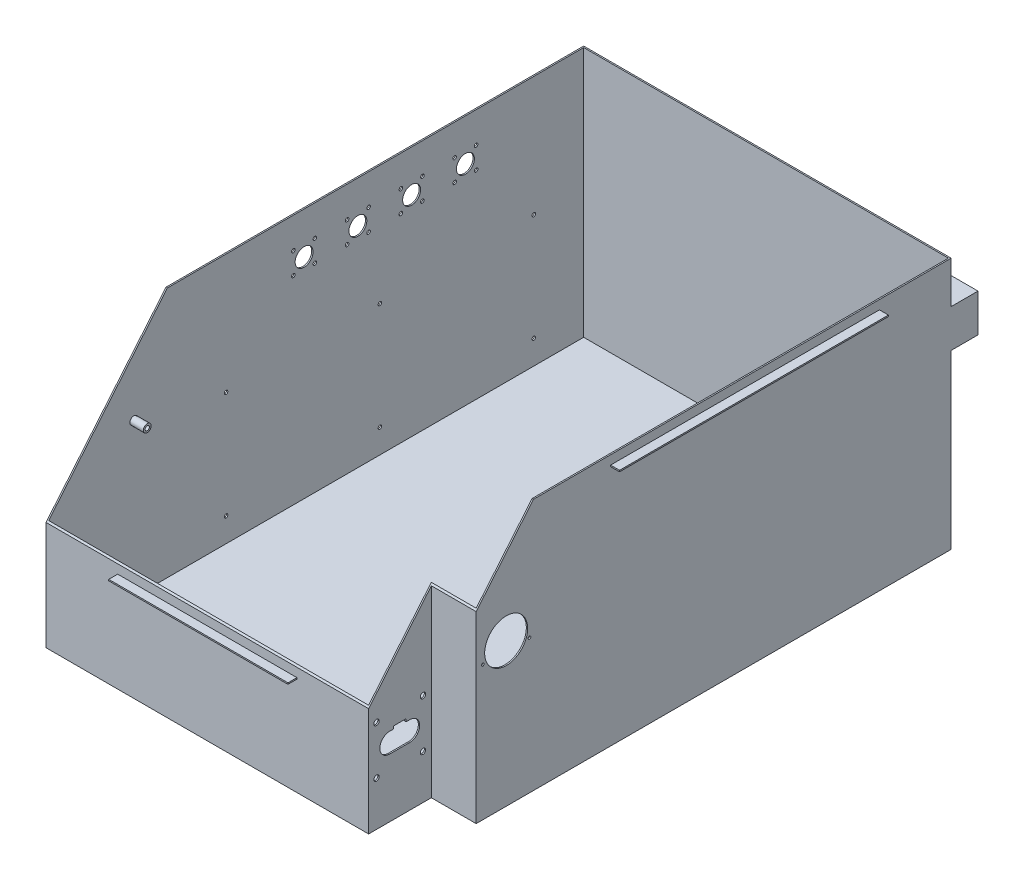
SolidWorks part; units mm, degrees
ref_plane "Front Plane" through (0, 0, 0) normal (0, 0, 1) x (1, 0, 0)
ref_plane "Top Plane" through (0, 0, 0) normal (0, 1, 0) x (1, 0, 0)
ref_plane "Right Plane" through (0, 0, 0) normal (1, 0, 0) x (0, 0, -1)
sketch "Sketch1" plane through (0, 0, 0) normal (0, 1, 0) x (1, 0, 0)
  line L1 (-205, 237.8263) -> (205, 237.8263)
  line L2 (-205, 237.8263) -> (-205, -362.1737)
  line L3 (-205, -362.1737) -> (155, -362.1737)
  line L4 (205, 237.8263) -> (205, -292.1737)
  line L6 (205, -292.1737) -> (155, -292.1737)
  line L7 (155, -292.1737) -> (155, -362.1737)
  line L8 (0, -55) -> (0, 55) construction
  point P1 (0, 237.8263)
  dimension "D1" = 600
  dimension "D2" = 410
  dimension "D5" = 70
  dimension "D6" = 50
extrude "Boss-Extrude1" add sketch "Sketch1" along normal blind 1.5
sketch "Sketch2" plane through (0, 1.5, 0) normal (0, 1, 0) x (1, 0, 0)
  line L60 (-203.5, 236.3263) -> (-203.5, -360.6737)
  line L61 (-203.5, -360.6737) -> (153.5, -360.6737)
  line L62 (153.5, -360.6737) -> (153.5, -290.6737)
  line L63 (153.5, -290.6737) -> (203.5, -290.6737)
  line L64 (203.5, -290.6737) -> (203.5, 236.3263)
  line L65 (203.5, 236.3263) -> (-203.5, 236.3263)
  line L66 (-205, 237.8263) -> (-205, -362.1737)
  line L67 (-205, -362.1737) -> (155, -362.1737)
  line L68 (155, -362.1737) -> (155, -292.1737)
  line L69 (155, -292.1737) -> (205, -292.1737)
  line L70 (205, -292.1737) -> (205, 237.8263)
  line L71 (205, 237.8263) -> (-205, 237.8263)
  line L72 (-205, 237.8263) -> (-205, -362.1737)
  line L73 (-205, -362.1737) -> (155, -362.1737)
  line L74 (155, -362.1737) -> (155, -292.1737)
  line L75 (155, -292.1737) -> (205, -292.1737)
  line L76 (205, -292.1737) -> (205, 237.8263)
  line L77 (205, 237.8263) -> (-205, 237.8263)
  dimension "D1" = 0
  dimension "D2" = 1.5
extrude "Boss-Extrude2" add sketch "Sketch2" along normal blind 280
sketch "Sketch3" plane through (-205, 0, 0) normal (-1, 0, 0) x (0, 0, 1)
  line L3 (362.1737, 281.5) -> (362.1737, 0) construction
  line L4 (362.1737, 121.1176) -> (228.1952, 281.5)
  line L6 (-237.8263, 281.5) -> (362.1737, 281.5) construction
  line L9 (362.1737, 281.5) -> (362.1737, 121.1176)
  line L10 (228.1952, 281.5) -> (362.1737, 281.5)
sketch "Sketch4" plane through (0, 0, -237.8263) normal (0, 0, -1) x (-1, 0, 0)
  line L0 (-205, 281.5) -> (-205, 0) construction
  line L1 (-205, 234.6761) -> (205, 234.6761)
  line L2 (-205, 234.6761) -> (-205, 192.2905)
  line L3 (-205, 192.2905) -> (205, 192.2905)
  line L4 (205, 234.6761) -> (205, 192.2905)
  line L5 (205, 281.5) -> (205, 0) construction
extrude "Boss-Extrude3" add sketch "Sketch4" along normal blind 30
extrude "Cut-Extrude1" cut sketch "Sketch3" against normal through all both and the other way through all
sketch "Sketch5" plane through (-205, 0, 0) normal (-1, 0, 0) x (0, 0, 1)
  line L0 (-116.3263, 223.1259) -> (-116.3263, 247.1259) construction
  line L5 (-116.3263, 223.1259) -> (-92.3263, 223.1259) construction
  line L6 (-116.3263, 247.1259) -> (-92.3263, 247.1259) construction
  line L7 (-92.3263, 223.1259) -> (-92.3263, 247.1259) construction
  line L8 (-116.3263, 223.1259) -> (-92.3263, 247.1259) construction
  line L9 (-116.3263, 247.1259) -> (-92.3263, 223.1259) construction
  line L10 (-56.3263, 223.1259) -> (-56.3263, 247.1259) construction
  line L11 (-56.3263, 223.1259) -> (-32.3263, 223.1259) construction
  line L12 (-56.3263, 247.1259) -> (-32.3263, 247.1259) construction
  line L13 (-32.3263, 223.1259) -> (-32.3263, 247.1259) construction
  line L14 (-56.3263, 223.1259) -> (-32.3263, 247.1259) construction
  line L15 (-56.3263, 247.1259) -> (-32.3263, 223.1259) construction
  line L16 (3.6737, 223.1259) -> (3.6737, 247.1259) construction
  line L17 (3.6737, 223.1259) -> (27.6737, 223.1259) construction
  line L18 (3.6737, 247.1259) -> (27.6737, 247.1259) construction
  line L19 (27.6737, 223.1259) -> (27.6737, 247.1259) construction
  line L20 (3.6737, 223.1259) -> (27.6737, 247.1259) construction
  line L21 (3.6737, 247.1259) -> (27.6737, 223.1259) construction
  line L22 (63.6737, 223.1259) -> (63.6737, 247.1259) construction
  line L23 (63.6737, 223.1259) -> (87.6737, 223.1259) construction
  line L24 (63.6737, 247.1259) -> (87.6737, 247.1259) construction
  line L25 (87.6737, 223.1259) -> (87.6737, 247.1259) construction
  line L26 (63.6737, 223.1259) -> (87.6737, 247.1259) construction
  line L27 (63.6737, 247.1259) -> (87.6737, 223.1259) construction
  line L28 (-236.3263, 281.5) -> (-236.3263, 1.5) construction
  circle A0 centre (-116.3263, 247.1259) radius 2
  circle A1 centre (-116.3263, 223.1259) radius 2
  circle A2 centre (-92.3263, 223.1259) radius 2
  circle A3 centre (-92.3263, 247.1259) radius 2
  circle A4 centre (-104.3263, 235.1259) radius 10
  circle A5 centre (-56.3263, 247.1259) radius 2
  circle A6 centre (-56.3263, 223.1259) radius 2
  circle A7 centre (-32.3263, 223.1259) radius 2
  circle A8 centre (-32.3263, 247.1259) radius 2
  circle A9 centre (-44.3263, 235.1259) radius 10
  circle A10 centre (3.6737, 247.1259) radius 2
  circle A11 centre (3.6737, 223.1259) radius 2
  circle A12 centre (27.6737, 223.1259) radius 2
  circle A13 centre (27.6737, 247.1259) radius 2
  circle A14 centre (15.6737, 235.1259) radius 10
  circle A15 centre (63.6737, 247.1259) radius 2
  circle A16 centre (63.6737, 223.1259) radius 2
  circle A17 centre (87.6737, 223.1259) radius 2
  circle A18 centre (87.6737, 247.1259) radius 2
  circle A19 centre (75.6737, 235.1259) radius 10
  point P9 (-104.3263, 235.1259)
  point P24 (-44.3263, 235.1259)
  point P38 (15.6737, 235.1259)
  point P52 (75.6737, 235.1259)
  dimension "D2" = 20
  dimension "D5" = 4
  dimension "D1" = 24
  dimension "D3" = 24
  dimension "D4" = 24
  dimension "D7" = 120
  dimension "D6" = 4
sketch "Sketch6" plane through (-203.5, 0, 0) normal (1, 0, 0) x (0, 0, -1)
  arc A0 (151.1392, 167.4539) -> (156.7272, 167.4539) centre (153.9332, 167.4539) ccw construction
  arc A1 (-68.8756, 167.4539) -> (-63.2876, 167.4539) centre (-66.0816, 167.4539) ccw construction
  arc A2 (-178.883, 167.4539) -> (-173.295, 167.4539) centre (-176.089, 167.4539) ccw construction
  arc A3 (151.1392, 167.4539) -> (156.7272, 167.4539) centre (153.9332, 167.4539) ccw
  arc A4 (-68.8756, 167.4539) -> (-63.2876, 167.4539) centre (-66.0816, 167.4539) ccw
  arc A5 (-178.883, 167.4539) -> (-173.295, 167.4539) centre (-176.089, 167.4539) ccw
  circle A6 centre (-176.089, 167.4539) radius 2.794
  circle A7 centre (-176.089, 167.4539) radius 4.5
  circle A8 centre (-64.4633, 167.4539) radius 4.5
  circle A9 centre (-64.4633, 167.4539) radius 2.794
  circle A10 centre (155.5515, 167.4539) radius 2.794
  circle A11 centre (155.5515, 167.4539) radius 4.5
  dimension "D1" = 9
extrude "Boss-Extrude4" [suppressed] add sketch "Sketch6" along normal blind 50 contours A4 A9 | A8 | A7 | A6 | A11 | A10
sketch "Sketch8" plane through (-203.5, 0, 0) normal (1, 0, 0) x (0, 0, -1)
  line L0 (236.3263, 1.5) -> (-360.6737, 1.5) construction
  line L1 (-360.6737, 122.9132) -> (-360.6737, 1.5) construction
  circle A0 centre (-265.6737, 172.2) radius 2.39
  circle A1 centre (-265.6737, 172.2) radius 4.39
  circle A2 centre (-265.6737, 16.5) radius 2.39
  circle A3 centre (-265.6737, 16.5) radius 4.39
  dimension "D3" = 4.78
  dimension "D4" = 2
  dimension "D1" = 155.7
  dimension "D2" = 15
  dimension "D5" = 95
extrude "Boss-Extrude5" add sketch "Sketch8" along normal blind 15
sketch "Sketch10" plane through (153.5, 0, 0) normal (-1, 0, 0) x (0, 0, 1)
  line L0 (316.1737, 86.5) -> (321.4237, 86.5) construction
  line L1 (316.1737, 66.5) -> (338.6737, 66.5) construction
  line L2 (338.6737, 76.5) -> (316.1737, 76.5) construction
  line L3 (360.6737, 1.5) -> (290.6737, 1.5) construction
  line L5 (321.4237, 86.5) -> (321.4237, 89.5) construction
  line L6 (321.4237, 89.5) -> (333.4237, 89.5) construction
  line L7 (333.4237, 86.5) -> (333.4237, 89.5) construction
  line L8 (360.6737, 122.9132) -> (360.6737, 1.5) construction
  line L9 (333.4237, 86.5) -> (338.6737, 86.5) construction
  line L10 (320.4237, 90.5) -> (334.4237, 90.5)
  line L11 (334.4237, 87.5) -> (334.4237, 90.5)
  line L12 (334.4237, 87.5) -> (338.6737, 87.5)
  line L13 (316.1737, 65.5) -> (338.6737, 65.5)
  line L14 (316.1737, 87.5) -> (320.4237, 87.5)
  line L15 (320.4237, 87.5) -> (320.4237, 90.5)
  line L17 (301.4737, 49.55) -> (353.3737, 49.55) construction
  line L18 (301.4737, 49.55) -> (301.4737, 103.45) construction
  line L19 (301.4737, 103.45) -> (353.3737, 103.45) construction
  line L20 (353.3737, 49.55) -> (353.3737, 103.45) construction
  line L21 (301.4737, 49.55) -> (353.3737, 103.45) construction
  line L22 (301.4737, 103.45) -> (353.3737, 49.55) construction
  arc A0 (316.1737, 86.5) -> (316.1737, 66.5) centre (316.1737, 76.5) ccw construction
  arc A1 (338.6737, 66.5) -> (338.6737, 86.5) centre (338.6737, 76.5) ccw construction
  arc A2 (338.6737, 65.5) -> (338.6737, 87.5) centre (338.6737, 76.5) ccw
  arc A3 (316.1737, 87.5) -> (316.1737, 65.5) centre (316.1737, 76.5) ccw
  circle A4 centre (301.4737, 103.45) radius 3
  circle A5 centre (353.3737, 103.45) radius 3
  circle A6 centre (301.4737, 49.55) radius 3
  circle A7 centre (353.3737, 49.55) radius 3
  point P12 (327.4237, 89.5)
  point P13 (327.4237, 76.5)
  point P26 (327.4237, 76.5)
  dimension "D1" = 65
  dimension "D2" = 22.5
  dimension "D6" = 20
  dimension "D10" = 6
  dimension "D3" = 22
  dimension "D4" = 12
  dimension "D5" = 3
  dimension "D8" = 51.9
  dimension "D9" = 53.9
  dimension "D7" = 1
extrude "Cut-Extrude2" cut sketch "Sketch10" against normal up to surface (1.5 mm away)
sketch "Sketch11" plane through (153.5, 0, 0) normal (-1, 0, 0) x (0, 0, 1)
  line L0 (298.4737, 103.43) -> (298.4737, 49.53) construction
  line L13 (316.1737, 66.5) -> (338.6737, 66.5) construction
  line L14 (316.1737, 86.5) -> (321.4237, 86.5) construction
  line L15 (316.1737, 66.5) -> (338.6737, 66.5)
  line L19 (316.1737, 86.5) -> (318.4237, 86.5)
  line L20 (334.4237, 90.5) -> (320.4237, 90.5)
  line L21 (334.4237, 90.5) -> (320.4237, 90.5)
  line L22 (334.4237, 87.5) -> (334.4237, 90.5)
  line L23 (334.4237, 87.5) -> (334.4237, 90.5)
  line L28 (330.4237, 86.5) -> (321.4237, 86.5)
  line L29 (316.2509, 66) -> (338.7144, 66)
  line L30 (330.9237, 86) -> (320.7529, 86)
  line L31 (330.9237, 86) -> (330.9237, 91)
  line L32 (330.9237, 91) -> (317.9237, 91)
  line L33 (317.9237, 91) -> (317.9237, 87)
  line L34 (316.2509, 87) -> (317.9237, 87)
  line L36 (298.4737, 103.43) -> (350.3737, 103.43) construction
  line L43 (334.4237, 90.5) -> (320.4237, 90.5)
  line L44 (334.4237, 90.5) -> (320.4237, 90.5)
  line L45 (334.4237, 87.5) -> (334.4237, 90.5)
  line L46 (334.4237, 87.5) -> (334.4237, 90.5)
  line L47 (338.6737, 87.5) -> (334.4237, 87.5)
  line L48 (338.6737, 87.5) -> (334.4237, 87.5)
  line L49 (316.1737, 65.5) -> (338.6737, 65.5)
  line L50 (316.1737, 65.5) -> (338.6737, 65.5)
  line L51 (320.4237, 87.5) -> (316.1737, 87.5)
  line L52 (320.4237, 87.5) -> (316.1737, 87.5)
  line L53 (320.4237, 90.5) -> (320.4237, 87.5)
  line L54 (320.4237, 90.5) -> (320.4237, 87.5)
  line L55 (334.4237, 90.5) -> (320.4237, 90.5)
  line L56 (334.4237, 90.5) -> (320.4237, 90.5)
  line L57 (334.4237, 87.5) -> (334.4237, 90.5)
  line L58 (334.4237, 87.5) -> (334.4237, 90.5)
  line L59 (338.6737, 87.5) -> (334.4237, 87.5)
  line L60 (338.6737, 87.5) -> (334.4237, 87.5)
  line L61 (316.1737, 65.5) -> (338.6737, 65.5)
  line L62 (316.1737, 65.5) -> (338.6737, 65.5)
  line L63 (320.4237, 87.5) -> (316.1737, 87.5)
  line L64 (320.4237, 87.5) -> (316.1737, 87.5)
  line L65 (320.4237, 90.5) -> (320.4237, 87.5)
  line L66 (320.4237, 90.5) -> (320.4237, 87.5)
  line L67 (330.4237, 86.5) -> (330.4237, 90.5) construction
  line L68 (330.4237, 90.5) -> (318.4237, 90.5) construction
  line L69 (318.4237, 90.5) -> (318.4237, 86.5) construction
  line L70 (338.6737, 87.5) -> (334.4237, 87.5)
  line L71 (338.6737, 87.5) -> (334.4237, 87.5)
  line L72 (316.1737, 65.5) -> (338.6737, 65.5)
  line L73 (316.1737, 65.5) -> (338.6737, 65.5)
  line L74 (320.4237, 87.5) -> (316.1737, 87.5)
  line L75 (320.4237, 87.5) -> (316.1737, 87.5)
  line L76 (320.4237, 90.5) -> (320.4237, 87.5)
  line L77 (320.4237, 90.5) -> (320.4237, 87.5)
  arc A4 (338.7144, 66) -> (320.7529, 86) centre (336.1498, 81.7622) ccw
  arc A5 (338.6737, 65.5) -> (338.6737, 87.5) centre (338.6737, 76.5) ccw
  arc A7 (338.6737, 65.5) -> (338.6737, 87.5) centre (338.6737, 76.5) ccw
  arc A9 (316.2509, 87) -> (316.2509, 66) centre (312.9721, 76.5) ccw
  circle A10 centre (298.4737, 103.43) radius 3
  circle A11 centre (298.4737, 49.53) radius 3
  circle A12 centre (350.3737, 103.43) radius 3
  circle A13 centre (350.3737, 49.53) radius 3
  arc A16 (338.6737, 66.5) -> (321.4237, 86.5) centre (336.1498, 81.7622) ccw construction
  arc A17 (338.6737, 65.5) -> (338.6737, 87.5) centre (338.6737, 76.5) ccw
  arc A18 (316.1737, 87.5) -> (316.1737, 65.5) centre (316.1737, 76.5) ccw
  arc A19 (316.1737, 87.5) -> (316.1737, 65.5) centre (316.1737, 76.5) ccw
  arc A20 (316.1737, 86.5) -> (316.1737, 66.5) centre (312.9721, 76.5) ccw construction
  arc A21 (338.6737, 65.5) -> (338.6737, 87.5) centre (338.6737, 76.5) ccw
  arc A22 (316.1737, 87.5) -> (316.1737, 65.5) centre (316.1737, 76.5) ccw
  arc A23 (316.1737, 87.5) -> (316.1737, 65.5) centre (316.1737, 76.5) ccw
  arc A24 (338.6737, 65.5) -> (338.6737, 87.5) centre (338.6737, 76.5) ccw
  arc A25 (338.6737, 65.5) -> (338.6737, 87.5) centre (338.6737, 76.5) ccw
  arc A26 (316.1737, 87.5) -> (316.1737, 65.5) centre (316.1737, 76.5) ccw
  arc A27 (316.1737, 87.5) -> (316.1737, 65.5) centre (316.1737, 76.5) ccw
  dimension "D5" = 6
  dimension "D6" = 51.9
  dimension "D7" = 53.9
  dimension "D1" = 0
  dimension "D2" = 0
  dimension "D3" = 0
  dimension "D4" = 0.5
extrude "Cut-Extrude3" [suppressed] cut sketch "Sketch11" against normal through all
sketch "Sketch14" plane through (153.5, 0, 0) normal (-1, 0, 0) x (0, 0, 1)
  line L0 (362.1737, 121.1176) -> (362.1737, 0) construction
  line L1 (362.1737, 0) -> (292.1737, 0) construction
  circle A0 centre (297.2737, 103.43) radius 3
  circle A1 centre (349.1737, 103.43) radius 3
  circle A2 centre (349.1737, 49.53) radius 3
  circle A3 centre (297.2737, 49.53) radius 3
  dimension "D5" = 6
  dimension "D1" = 51.9
  dimension "D2" = 53.9
  dimension "D3" = 13
  dimension "D4" = 103.43
extrude "Cut-Extrude4" [suppressed] cut sketch "Sketch14" against normal up to surface (1.5 mm away)
sketch "Sketch15" plane through (203.5, 0, 0) normal (-1, 0, 0) x (0, 0, 1)
  line L1 (-151.3263, 252.1363) -> (-136.3263, 252.1363)
  line L2 (-151.3263, 252.1363) -> (-151.3263, 250.6363)
  line L3 (-151.3263, 250.6363) -> (-136.3263, 250.6363)
  line L4 (-136.3263, 252.1363) -> (-136.3263, 250.6363)
  line L5 (-236.3263, 281.5) -> (-236.3263, 1.5) construction
  line L6 (126.6737, 252.1363) -> (146.6737, 252.1363)
  line L7 (126.6737, 250.6363) -> (146.6737, 250.6363)
  line L8 (126.6737, 252.1363) -> (126.6737, 250.6363)
  line L9 (146.6737, 252.1363) -> (146.6737, 250.6363)
  dimension "D1" = 1.5
  dimension "D2" = 15
  dimension "D3" = 85
  dimension "D4" = 363
  dimension "D5" = 20
extrude "Boss-Extrude6" add sketch "Sketch15" along normal blind 13
ref_plane "Plane1" through (0, 0, -131.3263) normal (0, 0, -1) x (-1, 0, 0)
sketch "Sketch17" plane through (0, 0, -136.3263) normal (0, 0, 1) x (1, 0, 0)
  line L0 (203.5, 250.6363) -> (203.5, 235.6363)
  line L1 (203.5, 281.5) -> (203.5, 206.7085) construction
  line L2 (203.5, 235.6363) -> (190.5, 250.6363)
  line L3 (190.5, 250.6363) -> (203.5, 250.6363)
  dimension "D1" = 15
extrude "Boss-Extrude7" add sketch "Sketch17" against normal blind 1.5
ref_plane "Plane2" through (0, 0, 126.6737) normal (0, 0, 1) x (1, 0, 0)
sketch "Sketch18" plane through (0, 0, 126.6737) normal (0, 0, 1) x (1, 0, 0)
  line L0 (203.5, 250.6363) -> (203.5, 235.6363)
  line L1 (203.5, 281.5) -> (203.5, 206.7085) construction
  line L2 (203.5, 235.6363) -> (190.5, 250.6363)
  line L3 (190.5, 250.6363) -> (203.5, 250.6363)
  dimension "D1" = 15
extrude "Boss-Extrude8" add sketch "Sketch18" along normal blind 1.5
sketch "Sketch20" plane through (0, 252.1363, 0) normal (0, 1, 0) x (1, 0, 0)
  line L1 (190.5, 151.3263) -> (203.5, 151.3263) construction
  line L2 (190.5, 136.3263) -> (190.5, 151.3263) construction
  line L3 (190.5, -146.6737) -> (203.5, -146.6737) construction
  line L4 (190.5, -146.6737) -> (190.5, -126.6737) construction
  circle A0 centre (198, 144.3263) radius 2.4159
  circle A1 centre (200.5, -139.6737) radius 2
  dimension "D3" = 4
  dimension "D1" = 7
  dimension "D2" = 7.5
  dimension "D4" = 7
  dimension "D5" = 10
extrude "Cut-Extrude5" cut sketch "Sketch20" against normal up to surface (1.5 mm away) up to face at (197, 250.6363, -144.5763)
extrude "Cut-Extrude7" cut sketch "Sketch5" against normal up to surface (1.5 mm away) up to face at (-203.5, 16.5, 261.2837)
sketch "Sketch21" plane through (0, 0, -237.8263) normal (0, 0, -1) x (-1, 0, 0)
  line L0 (-205, 281.5) -> (205, 281.5) construction
  line L1 (-150, 271.5) -> (150, 271.5)
  line L2 (-150, 271.5) -> (-150, 270)
  line L3 (-150, 270) -> (150, 270)
  line L4 (150, 271.5) -> (150, 270)
  point P6 (0, 281.5)
  point P7 (0, 271.5)
  dimension "D1" = 1.5
  dimension "D2" = 300
  dimension "D3" = 10
extrude "Boss-Extrude9" add sketch "Sketch21" along normal blind 10
sketch "Sketch22" plane through (-205, 0, 0) normal (-1, 0, 0) x (0, 0, 1)
  line L0 (-237.8263, 281.5) -> (228.1952, 281.5) construction
  line L1 (-157.8263, 271.5) -> (142.1737, 271.5)
  line L2 (-157.8263, 271.5) -> (-157.8263, 270)
  line L3 (-157.8263, 270) -> (142.1737, 270)
  line L4 (142.1737, 271.5) -> (142.1737, 270)
  line L5 (-237.8263, 281.5) -> (-237.8263, 234.6761) construction
  dimension "D1" = 1.5
  dimension "D2" = 10
  dimension "D3" = 80
  dimension "D4" = 300
extrude "Boss-Extrude10" add sketch "Sketch22" along normal blind 10
ref_plane "Plane3" through (0, 0, -77.8263) normal (0, 0, -1) x (-1, 0, 0)
sketch "Sketch23" plane through (0, 0, -77.8263) normal (0, 0, -1) x (-1, 0, 0)
  line L0 (215, 270) -> (205, 270) construction
  line L1 (215, 270) -> (205, 270)
  line L2 (215, 270) -> (205, 260)
  line L3 (205, 281.5) -> (205, 234.6761) construction
  line L4 (205, 260) -> (205, 270)
  dimension "D1" = 10
extrude "Boss-Extrude11" add sketch "Sketch23" along normal mid plane 1.5
ref_plane "Plane4" through (0, 0, 52.1737) normal (0, 0, 1) x (1, 0, 0)
sketch "Sketch24" plane through (0, 0, 52.1737) normal (0, 0, 1) x (1, 0, 0)
  line L6 (-215, 270) -> (-205, 260)
  line L7 (-205, 260) -> (-205, 270)
  line L8 (-205, 270) -> (-215, 270)
  line L9 (-215, 270) -> (-205, 260)
  line L10 (-205, 260) -> (-205, 270)
  line L11 (-205, 270) -> (-215, 270)
  dimension "D1" = 0
extrude "Boss-Extrude12" add sketch "Sketch24" along normal mid plane 1.5
ref_plane "Plane5" through (100, 0, 0) normal (1, 0, 0) x (0, 0, -1)
sketch "Sketch25" plane through (100, 0, 0) normal (1, 0, 0) x (0, 0, -1)
  line L0 (247.8263, 270) -> (237.8263, 270)
  line L1 (237.8263, 270) -> (237.8263, 260)
  line L2 (237.8263, 281.5) -> (237.8263, 234.6761) construction
  line L3 (237.8263, 260) -> (247.8263, 270)
  dimension "D1" = 10
extrude "Boss-Extrude13" add sketch "Sketch25" along normal mid plane 1.5
ref_plane "Plane6" through (-100, 0, 0) normal (-1, 0, 0) x (0, 0, 1)
sketch "Sketch26" plane through (-100, 0, 0) normal (-1, 0, 0) x (0, 0, 1)
  line L3 (-247.8263, 270) -> (-237.8263, 260)
  line L4 (-237.8263, 260) -> (-237.8263, 270)
  line L5 (-237.8263, 270) -> (-247.8263, 270)
  line L6 (-247.8263, 270) -> (-237.8263, 260)
  line L7 (-237.8263, 260) -> (-237.8263, 270)
  line L8 (-237.8263, 270) -> (-247.8263, 270)
  dimension "D1" = 0
extrude "Boss-Extrude14" add sketch "Sketch26" along normal mid plane 1.5
mirror "Mirror1" about plane through (0, 0, 0) normal (1, 0, 0) of "Boss-Extrude11", "Boss-Extrude12", "Boss-Extrude10"
sketch "Sketch27" plane through (0, 0, 362.1737) normal (0, 0, 1) x (1, 0, 0)
  line L0 (155, 121.1176) -> (-205, 121.1176) construction
  line L1 (-125, 111.1176) -> (75, 111.1176)
  line L2 (-125, 111.1176) -> (-125, 109.6176)
  line L3 (-125, 109.6176) -> (75, 109.6176)
  line L4 (75, 111.1176) -> (75, 109.6176)
  line L5 (155, 121.1176) -> (-205, 121.1176) construction
  point P6 (-25, 121.1176)
  point P7 (-25, 111.1176)
  dimension "D1" = 1.5
  dimension "D2" = 200
  dimension "D3" = 10
extrude "Boss-Extrude15" add sketch "Sketch27" along normal blind 10
ref_plane "Plane7" through (-95, 0, 0) normal (-1, 0, 0) x (0, 0, 1)
sketch "Sketch28" plane through (-95, 0, 0) normal (-1, 0, 0) x (0, 0, 1)
  line L0 (372.1737, 109.6176) -> (362.1737, 109.6176)
  line L1 (362.1737, 109.6176) -> (362.1737, 99.6176)
  line L2 (362.1737, 121.1176) -> (362.1737, 0) construction
  line L3 (362.1737, 99.6176) -> (372.1737, 109.6176)
  dimension "D1" = 10
extrude "Boss-Extrude16" add sketch "Sketch28" along normal mid plane 1.5
ref_plane "Plane8" through (45, 0, 0) normal (1, 0, 0) x (0, 0, -1)
sketch "Sketch29" plane through (45, 0, 0) normal (1, 0, 0) x (0, 0, -1)
  line L3 (-372.1737, 109.6176) -> (-362.1737, 99.6176)
  line L4 (-362.1737, 99.6176) -> (-362.1737, 109.6176)
  line L5 (-362.1737, 109.6176) -> (-372.1737, 109.6176)
  line L6 (-372.1737, 109.6176) -> (-362.1737, 99.6176)
  line L7 (-362.1737, 99.6176) -> (-362.1737, 109.6176)
  line L8 (-362.1737, 109.6176) -> (-372.1737, 109.6176)
  dimension "D1" = 0
extrude "Boss-Extrude17" add sketch "Sketch29" along normal mid plane 1.5
sketch "Sketch30" plane through (205, 0, 0) normal (1, 0, 0) x (0, 0, -1)
  line L1 (-292.1737, 0) -> (237.8263, 0) construction
  line L2 (-292.1737, 204.9129) -> (-292.1737, 0) construction
  circle A0 centre (-258.6737, 160) radius 24
  circle A1 centre (-284.6737, 150) radius 1.5
  circle A2 centre (-232.6737, 150) radius 1.5
  dimension "D1" = 48
  dimension "D2" = 3
  dimension "D3" = 3
  dimension "D4" = 26
  dimension "D5" = 10
  dimension "D6" = 26
  dimension "D7" = 10
  dimension "D8" = 160
  dimension "D9" = 33.5
extrude "Cut-Extrude8" cut sketch "Sketch30" against normal up to surface (1.5 mm away) up to face at (203.5, 246.1363, -141.8263)
sketch "Sketch31" plane through (0, 0, 0) normal (0, -1, 0) x (1, 0, 0)
  line L0 (205, -237.8263) -> (-205, -237.8263) construction
  line L1 (205, -213.8263) -> (225, -213.8263)
  line L2 (205, -213.8263) -> (205, -237.8263)
  line L3 (205, -237.8263) -> (225, -237.8263)
  line L4 (225, -213.8263) -> (225, -237.8263)
  line L64 (205, 228.1952) -> (205, -237.8263) construction
  line L65 (205, -88.0763) -> (225, -88.0763)
  line L66 (205, -88.0763) -> (205, -112.0763)
  line L67 (205, -112.0763) -> (225, -112.0763)
  line L68 (225, -88.0763) -> (225, -112.0763)
  line L69 (205, 37.6737) -> (225, 37.6737)
  line L70 (205, 37.6737) -> (205, 13.6737)
  line L71 (205, 13.6737) -> (225, 13.6737)
  line L72 (225, 37.6737) -> (225, 13.6737)
  line L73 (205, 163.4237) -> (225, 163.4237)
  line L74 (205, 163.4237) -> (205, 139.4237)
  line L75 (205, 139.4237) -> (225, 139.4237)
  line L76 (225, 163.4237) -> (225, 139.4237)
  line L77 (205, 289.1737) -> (225, 289.1737)
  line L78 (205, 289.1737) -> (205, 265.1737)
  line L79 (205, 265.1737) -> (225, 265.1737)
  line L80 (225, 289.1737) -> (225, 265.1737)
  circle A0 centre (225, -225.8263) radius 12
  circle A1 centre (225, -225.8263) radius 4
  circle A30 centre (225, -100.0763) radius 12
  circle A31 centre (225, -100.0763) radius 4
  circle A32 centre (225, 25.6737) radius 12
  circle A33 centre (225, 25.6737) radius 4
  circle A34 centre (225, 151.4237) radius 12
  circle A35 centre (225, 151.4237) radius 4
  circle A36 centre (225, 277.1737) radius 12
  circle A37 centre (225, 277.1737) radius 4
  dimension "D3" = 8
  dimension "D1" = 24
  dimension "D2" = 20
  dimension "D5" = 101.75
  dimension "D4" = 5
extrude "Boss-Extrude18" [suppressed] add sketch "Sketch31" against normal blind 1.5 separate body
sketch "Sketch33" plane through (-205, 0, 0) normal (-1, 0, 0) x (0, 0, 1)
  line L0 (-237.8263, 192.2905) -> (-237.8263, 0) construction
  line L1 (-237.8263, 0) -> (362.1737, 0) construction
  circle A0 centre (-180.6263, 147.77) radius 2
  circle A1 centre (-180.6263, 28.39) radius 2
  circle A2 centre (-8.9263, 147.77) radius 2
  circle A3 centre (-8.9263, 28.39) radius 2
  circle A4 centre (162.7737, 147.77) radius 2
  circle A5 centre (162.7737, 28.39) radius 2
  dimension "D3" = 4
  dimension "D1" = 57.2
  dimension "D2" = 119.38
  dimension "D4" = 28.39
  dimension "D5" = 3
extrude "Cut-Extrude9" cut sketch "Sketch33" against normal up to surface (1.5 mm away) up to face at (-203.5, 223.1259, 25.6737)
mirror "Mirror2" [suppressed] about plane through (0, 0, 0) normal (1, 0, 0)
